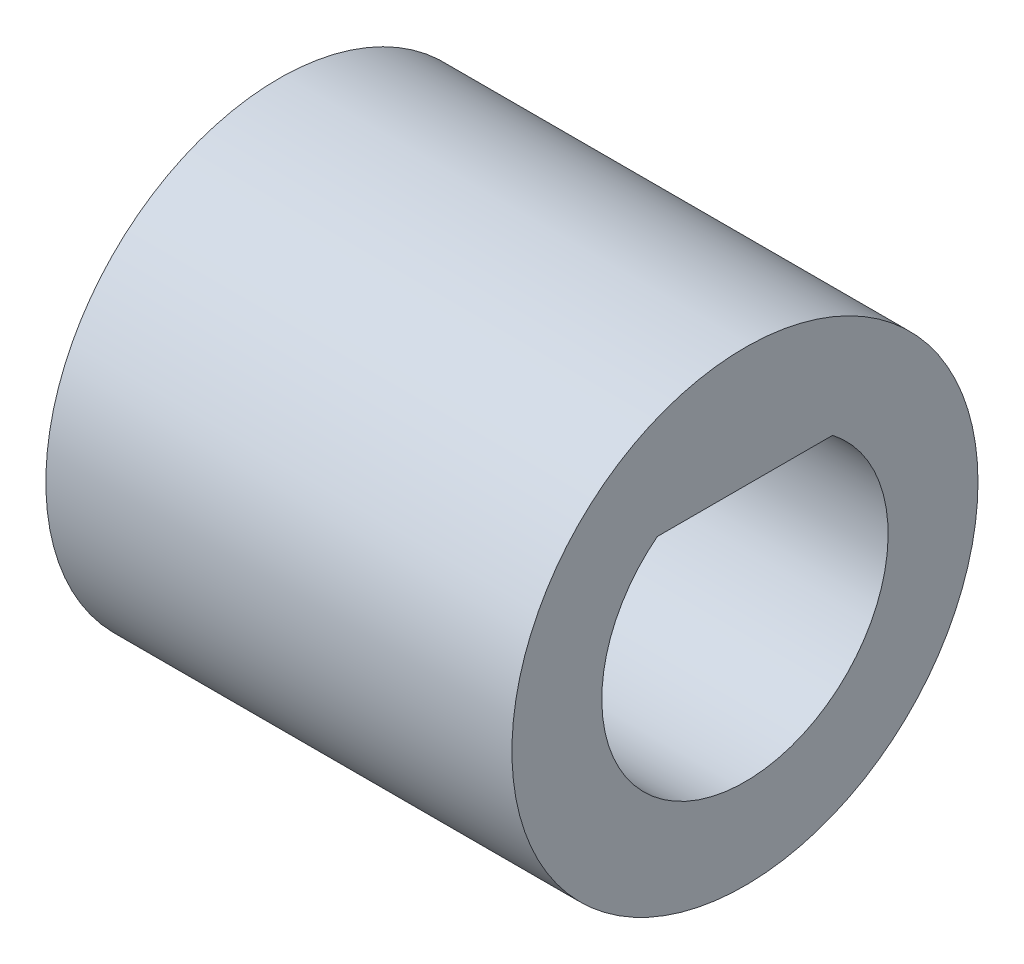
SolidWorks part; units mm, degrees
ref_plane "Front Plane" through (0, 0, 0) normal (0, 0, 1) x (1, 0, 0)
ref_plane "Top Plane" through (0, 0, 0) normal (0, 1, 0) x (1, 0, 0)
ref_plane "Right Plane" through (0, 0, 0) normal (1, 0, 0) x (0, 0, -1)
sketch "Sketch1" plane through (0, 0, 0) normal (1, 0, 0) x (0, 0, -1)
  line L0 (-1.9, 1.8473) -> (-1.9, -1.8473)
  line L1 (1.9, 1.8473) -> (1.9, -1.8473)
  arc A0 (-1.9, -1.8473) -> (1.9, -1.8473) centre (0, 0) ccw
  arc A2 (1.9, 1.8473) -> (-1.9, 1.8473) centre (0, 0) ccw
  dimension "D3" = 5.3
  dimension "D1" = 3.8
  dimension "D2" = 1.9
sketch "Sketch5" plane through (0, 0, 0) normal (1, 0, 0) x (0, 0, -1)
  line L0 (-1.3162, 1.7) -> (1.3162, 1.7) construction
  arc A0 (-1.3162, 1.7) -> (1.3162, 1.7) centre (0, 0) ccw construction
  circle A1 centre (0, 0) radius 3.5
  dimension "D1" = 4.3
  dimension "D3" = 7
  dimension "D2" = 1.7
extrude "Boss-Extrude2" add sketch "Sketch5" along normal blind 7 contours A1
sketch "Sketch7" plane through (7, 0, 0) normal (1, 0, 0) x (0, 0, -1)
  line L0 (-1.3162, 1.7) -> (1.3162, 1.7)
  arc A0 (-1.3162, 1.7) -> (1.3162, 1.7) centre (0, 0) ccw
  arc A1 (-1.3162, 1.7) -> (1.3162, 1.7) centre (0, 0) ccw construction
extrude "Cut-Extrude1" cut sketch "Sketch7" against normal blind 5
equation "\"D2@Sketch1\"=\"D1@Sketch1\"/2"
